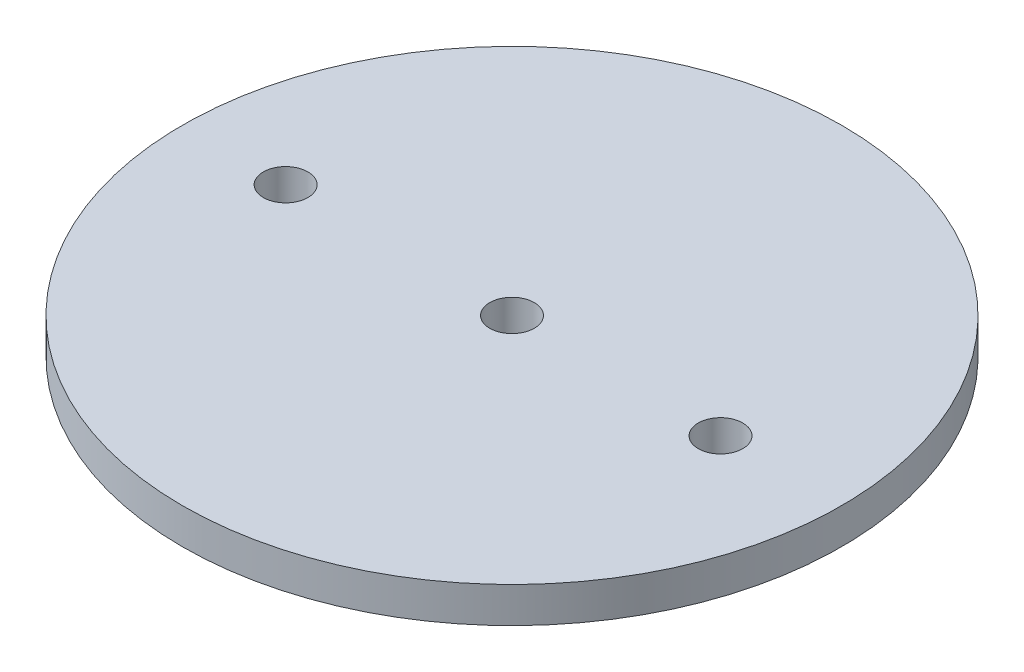
SolidWorks part; units mm, degrees
ref_plane "Front Plane" through (0, 0, 0) normal (0, 0, 1) x (1, 0, 0)
ref_plane "Top Plane" through (0, 0, 0) normal (0, 1, 0) x (1, 0, 0)
ref_plane "Right Plane" through (0, 0, 0) normal (1, 0, 0) x (0, 0, -1)
sketch "Sketch1" plane through (0, 0, 0) normal (0, 1, 0) x (1, 0, 0)
  circle A0 centre (0, 0) radius 46.99
  dimension "D1" = 93.98
extrude "Boss-Extrude1" add sketch "Sketch1" along normal blind 5.08
sketch "Sketch2" plane through (0, 5.08, 0) normal (0, 1, 0) x (1, 0, 0)
  line L0 (-46.99, 0) -> (46.99, 0) construction
  circle A0 centre (0, 0) radius 46.99 construction
  circle A1 centre (-32.278, 0) radius 3.175
  circle A2 centre (0, 0) radius 3.175
  circle A3 centre (29.73, 0) radius 3.175
  dimension "D1" = 6.35
extrude "Cut-Extrude1" cut sketch "Sketch2" against normal through all
